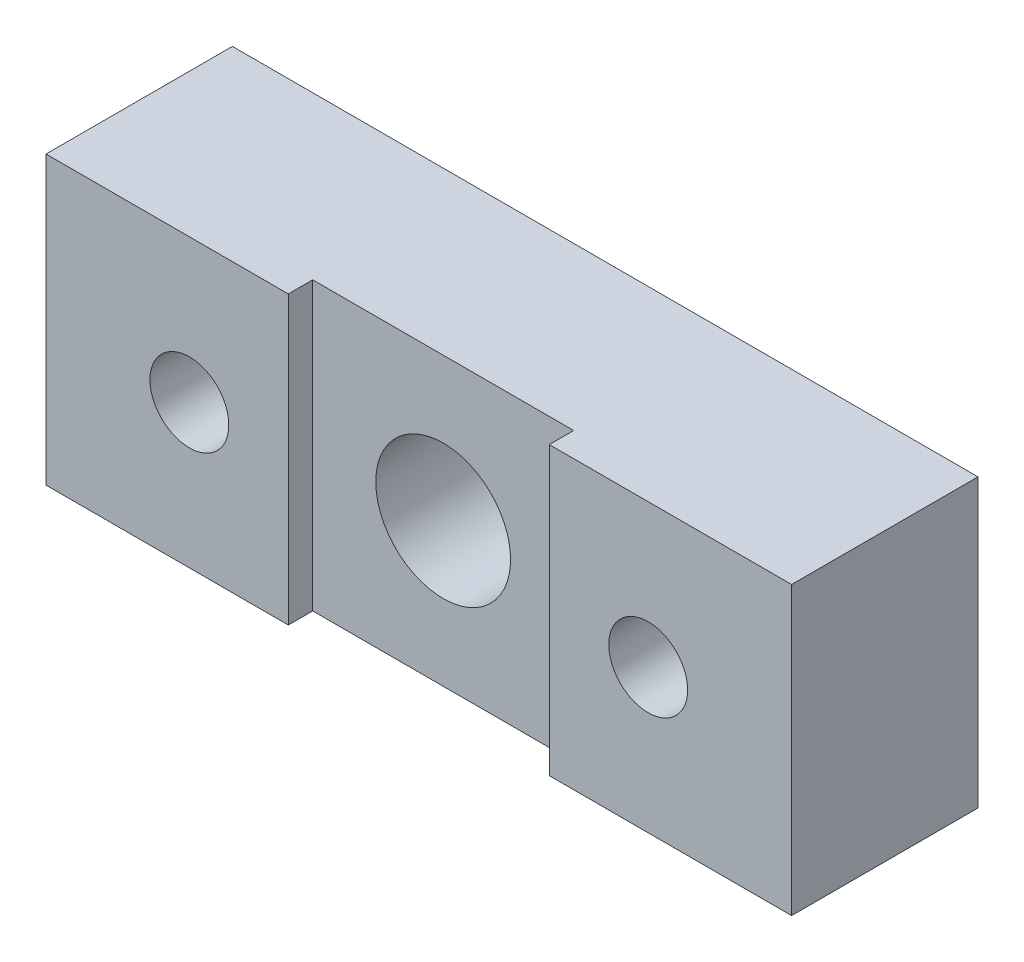
SolidWorks part; units mm, degrees
ref_plane "前视基准面" through (0, 0, 0) normal (0, 0, 1) x (1, 0, 0)
ref_plane "上视基准面" through (0, 0, 0) normal (0, 1, 0) x (1, 0, 0)
ref_plane "右视基准面" through (0, 0, 0) normal (1, 0, 0) x (0, 0, -1)
sketch "草图1" plane through (0, 0, 0) normal (0, 0, 1) x (1, 0, 0)
  line L0 (-16, 0) -> (16, 0) construction
  line L1 (-26, 10) -> (26, 10)
  line L2 (-26, 10) -> (-26, -10)
  line L3 (-26, -10) -> (26, -10)
  line L4 (26, 10) -> (26, -10)
  line L5 (-26, 10) -> (26, -10) construction
  line L6 (-26, -10) -> (26, 10) construction
  circle A0 centre (-16, 0) radius 2.75
  circle A1 centre (16, 0) radius 2.75
  circle A2 centre (0, 0) radius 4.7
  point P0 (0, 0)
  dimension "D5" = 5.5
  dimension "D6" = 9.4
  dimension "D1" = 20
  dimension "D2" = 52
  dimension "D3" = 16
  dimension "D4" = 32
extrude "凸台-拉伸1" add sketch "草图1" along normal blind 13
sketch "草图2" plane through (0, 0, 0) normal (0, 0, -1) x (-1, 0, 0)
  circle A0 centre (-16, 0) radius 4.5
  circle A1 centre (16, 0) radius 4.5
  dimension "D1" = 9
extrude "切除-拉伸1" cut sketch "草图2" against normal blind 5
sketch "草图3" plane through (0, 0, 13) normal (0, 0, 1) x (1, 0, 0)
  line L0 (26, 10) -> (-26, 10) construction
  line L1 (9.1, -10) -> (-9.1, -10)
  line L2 (9.1, -10) -> (9.1, 10)
  line L3 (9.1, 10) -> (-9.1, 10)
  line L4 (-9.1, -10) -> (-9.1, 10)
  line L5 (9.1, -10) -> (-9.1, 10) construction
  line L6 (9.1, 10) -> (-9.1, -10) construction
  point P0 (0, 0)
  dimension "D1" = 18.2
extrude "切除-拉伸2" cut sketch "草图3" against normal blind 1.7
fillet "圆角1" radius 1 2 edges at (13.25, 0, 5) (-18.75, 0, 5)
